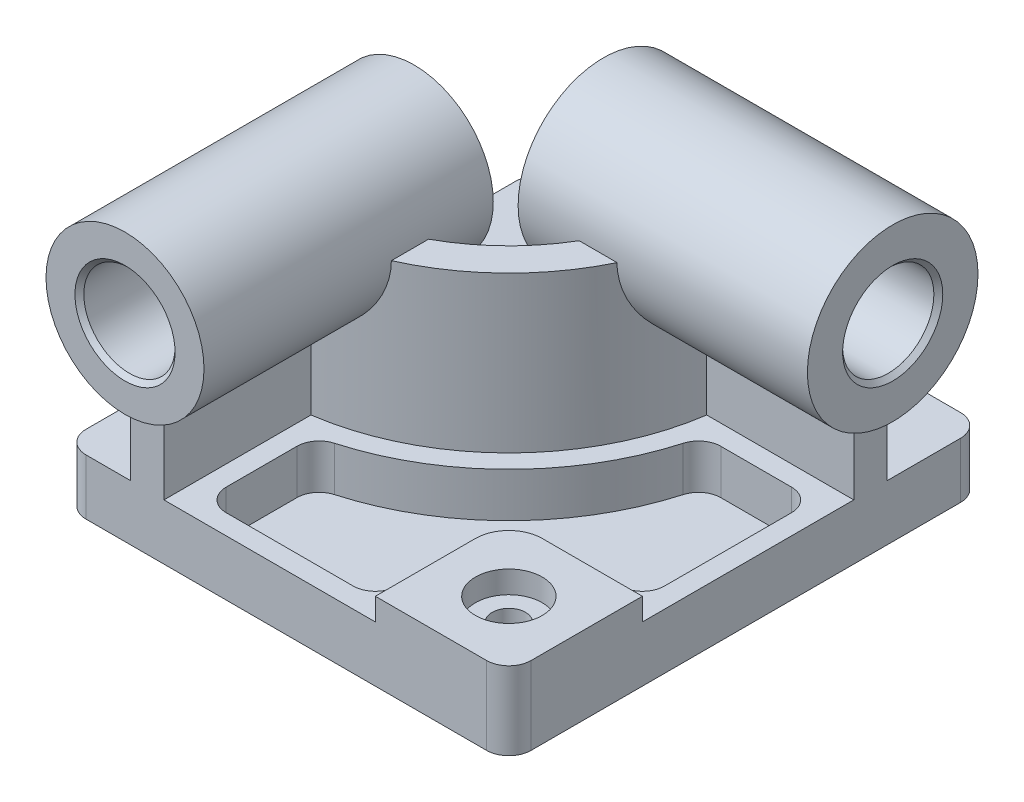
SolidWorks part; units mm, degrees
material "Alloy Steel"
ref_plane "Front Plane" through (0, 0, 0) normal (0, 0, 1) x (1, 0, 0)
ref_plane "Top Plane" through (0, 0, 0) normal (0, 1, 0) x (1, 0, 0)
ref_plane "Right Plane" through (0, 0, 0) normal (1, 0, 0) x (0, 0, -1)
sketch "Sketch1" plane through (0, 0, 0) normal (0, 1, 0) x (1, 0, 0)
  line L0 (0, 0) -> (0, -170) construction
  line L1 (-20, 43) -> (160, 43)
  line L2 (-30, 33) -> (-30, -160)
  line L3 (-20, -170) -> (160, -170)
  line L4 (170, 33) -> (170, -160)
  line L6 (21.1729, -100.3509) -> (22.0551, -100.3509) construction
  line L8 (0, 0) -> (170, 0) construction
  arc A0 (-20, 43) -> (-30, 33) centre (-20, 33) ccw
  arc A1 (-30, -160) -> (-20, -170) centre (-20, -160) ccw
  arc A2 (160, -170) -> (170, -160) centre (160, -160) ccw
  arc A3 (160, 43) -> (170, 33) centre (160, 33) cw
  dimension "D5" = 10
  dimension "D1" = 170
  dimension "D2" = 170
  dimension "D3" = 213
  dimension "D4" = 200
extrude "Boss-Extrude1" add sketch "Sketch1" along normal blind 25
sketch "Sketch2" plane through (0, 25, 0) normal (0, 1, 0) x (1, 0, 0)
  line L0 (0, -90) -> (0, -170)
  line L1 (-20, -170) -> (160, -170) construction
  line L2 (90, 0) -> (170, 0)
  line L3 (170, -160) -> (170, 33) construction
  line L4 (15, -103.923) -> (15, -170)
  line L5 (103.923, -15) -> (170, -15)
  line L6 (170, 0) -> (170, -15)
  line L7 (0, -170) -> (15, -170)
  arc A0 (0, -90) -> (90, 0) centre (0, 0) ccw
  arc A1 (15, -103.923) -> (103.923, -15) centre (0, 0) ccw
  dimension "D1" = 80
  dimension "D2" = 15
extrude "Boss-Extrude2" add sketch "Sketch2" along normal blind 95 from surface at -25 starting at face at (70, 0, 63.5)
sketch "Sketch3" plane through (0, 25, 0) normal (0, 1, 0) x (1, 0, 0)
  line L0 (15, -170) -> (160, -170) construction
  line L1 (125, -110) -> (170, -110)
  line L2 (110, -125) -> (110, -170)
  line L3 (110, -170) -> (160, -170)
  line L4 (170, -110) -> (170, -160)
  line L5 (170, -160) -> (170, -15) construction
  arc A0 (160, -170) -> (170, -160) centre (160, -160) ccw construction
  arc A1 (160, -170) -> (170, -160) centre (160, -160) ccw
  arc A2 (125, -110) -> (110, -125) centre (125, -125) ccw
  dimension "D3" = 15
  dimension "D1" = 60
  dimension "D2" = 60
extrude "Boss-Extrude3" add sketch "Sketch3" along normal blind 10
hole_wizard "CBORE for M8 Hex Head Bolt1" positions "Sketch5" profile "Sketch4" counterbore size "M8" standard "ANSI Metric" end condition through all
sketch "Sketch5" plane through (0, 35, 0) normal (0, 1, 0) x (1, 0, 0)
  line L0 (110, -170) -> (160, -170) construction
  line L2 (170, -160) -> (170, -110) construction
  point P0 (140, -140)
  dimension "D1" = 30
  dimension "D2" = 30
sketch "Sketch4" plane through (140, 35, 140) normal (1, 0, 0) x (0, 0, 1)
  line L0 (0, 0) -> (0, 35)
  line L1 (0, 35) -> (7.5, 35)
  line L3 (7.5, 35) -> (7.5, 10)
  line L4 (7.5, 10) -> (15, 10)
  line L5 (15, 10) -> (15, 0)
  line L7 (15, 0) -> (0, 0)
  line L11 (0, -6.35) -> (0, 107.95) construction
  dimension "Thru Hole Dia." = 15
  dimension "Thru Hole Depth" = 35
  dimension "C'Bore Dia." = 30
  dimension "C'Bore Depth" = 10
sketch "Sketch6" plane through (0, 25, 0) normal (0, 1, 0) x (1, 0, 0)
  line L6 (101, -161) -> (101, -125)
  line L7 (101, -151) -> (101, -125)
  line L8 (125, -101) -> (161, -101)
  line L9 (125, -101) -> (151, -101)
  line L10 (161, -24) -> (111.4451, -24)
  line L11 (151, -24) -> (119.2476, -24)
  line L12 (24, -161) -> (101, -161)
  line L13 (24, -111.4451) -> (24, -161)
  line L14 (24, -119.2476) -> (24, -151)
  line L15 (161, -101) -> (161, -24)
  line L18 (34, -161) -> (91, -161)
  line L21 (161, -91) -> (161, -34)
  arc A0 (161, -91) -> (151, -101) centre (151, -91) cw
  arc A1 (101, -151) -> (91, -161) centre (91, -151) cw
  arc A2 (24, -119.2476) -> (31.2581, -109.6309) centre (34, -119.2476) cw
  arc A3 (109.6309, -31.2581) -> (119.2476, -24) centre (119.2476, -34) cw
  arc A4 (125, -101) -> (101, -125) centre (125, -125) ccw
  arc A5 (24, -111.4451) -> (111.4451, -24) centre (0, 0) ccw
  arc A6 (125, -101) -> (101, -125) centre (125, -125) ccw
  arc A7 (31.2581, -109.6309) -> (109.6309, -31.2581) centre (0, 0) ccw
  arc A8 (161, -34) -> (151, -24) centre (151, -34) ccw
  arc A9 (34, -161) -> (24, -151) centre (34, -151) cw
  dimension "D2" = 10
  dimension "D3" = 10
  dimension "D1" = 9
extrude "Cut-Extrude1" cut sketch "Sketch6" against normal offset from surface (20 mm away) 5 up to face at (140, 0, 147.5)
sketch "Sketch7" plane through (0, 0, 170) normal (0, 0, 1) x (1, 0, 0)
  line L0 (0, 95) -> (15, 95) construction
  circle A0 centre (7.5, 95) radius 35.5
  dimension "D1" = 71
extrude "Boss-Extrude4" add sketch "Sketch7" against normal blind 130 from offset 10
sketch "Sketch8" plane through (170, 0, 0) normal (1, 0, 0) x (0, 0, -1)
  line L0 (-15, 95) -> (0, 95) construction
  circle A0 centre (-7.5, 95) radius 38.3333
  dimension "D1" = 76.6667
extrude "Boss-Extrude5" add sketch "Sketch8" against normal blind 130 from offset 10
sketch "Sketch9" plane through (0, 0, 180) normal (0, 0, 1) x (1, 0, 0)
  circle A0 centre (7.5, 95) radius 20.5
  dimension "D1" = 41
extrude "Cut-Extrude2" cut sketch "Sketch9" against normal up to next
sketch "Sketch10" plane through (180, 0, 0) normal (1, 0, 0) x (0, 0, -1)
  circle A0 centre (-7.5, 95) radius 20.5
  dimension "D1" = 41
extrude "Cut-Extrude3" cut sketch "Sketch10" against normal up to next
chamfer "Chamfer1" distance 2 angle 45 4 edges at (50, 95, -13) (28, 95, 50) (180, 95, -13) (28, 95, 180)
equation "\"A\" = 213"
equation "\"D1@Sketch1\"=\"C\""
equation "\"D2@Sketch1\"=\"C\""
equation "\"B\" = 200"
equation "\"D3@Sketch1\"=\"A\""
equation "\"C\" = 170"
equation "\"D4@Sketch1\"=\"B\""
equation "\"D1@Sketch7\"=\"X\""
equation "\"D\" = 130"
equation "\"D1@Boss-Extrude4\"=\"D\""
equation "\"D1@Sketch8\"=\"Y\""
equation "\"D1@Boss-Extrude5\"=\"D\""
equation "\"E\"= 41"
equation "\"D1@Sketch9\"=\"E\""
equation "\"D1@Sketch10\"=\"E\""
equation "\"X\"= \"A\" / 3"
equation "\"Y\"= \"B\" / 3 + 10"
